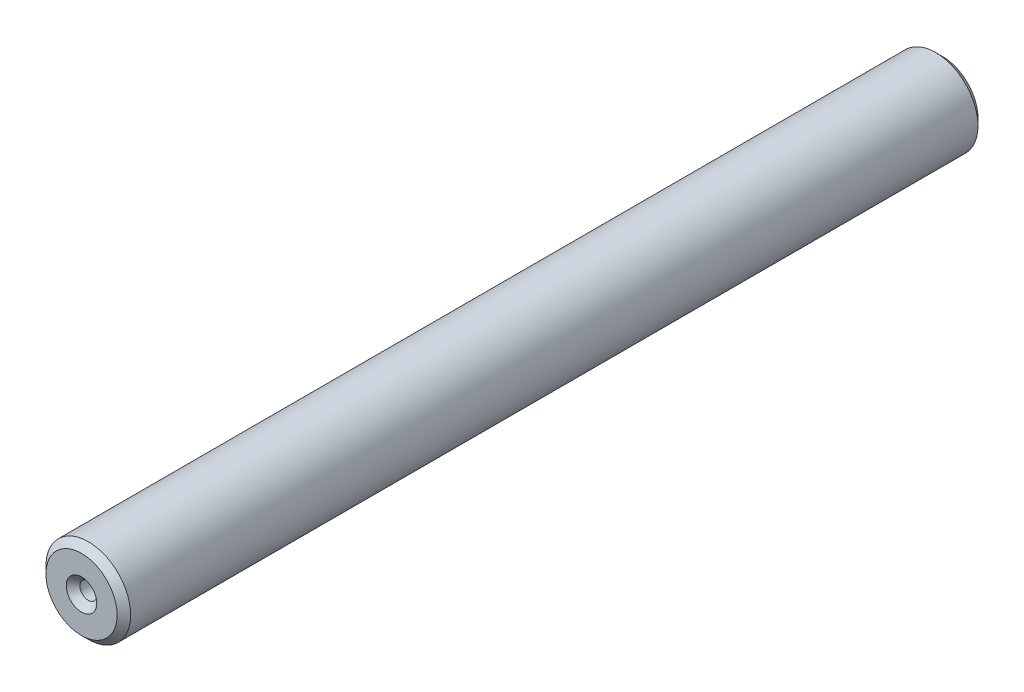
SolidWorks part; units mm, degrees
ref_plane "Front Plane" through (0, 0, 0) normal (0, 0, 1) x (1, 0, 0)
ref_plane "Top Plane" through (0, 0, 0) normal (0, 1, 0) x (1, 0, 0)
ref_plane "Right Plane" through (0, 0, 0) normal (1, 0, 0) x (0, 0, -1)
sketch "Sketch1" plane through (0, 0, 0) normal (0, 0, 1) x (1, 0, 0)
  circle A0 centre (0, 0) radius 2.5
  circle A1 centre (0, 0) radius 12.5
  dimension "D2" = 5
  dimension "D1" = 10
extrude "Boss-Extrude1" add sketch "Sketch1" along normal mid plane 254
chamfer "Chamfer1" distance 2 angle 45 4 edges at (2.5, 0, -127) (12.5, 0, -127) (2.5, 0, 127) (12.5, 0, 127)
